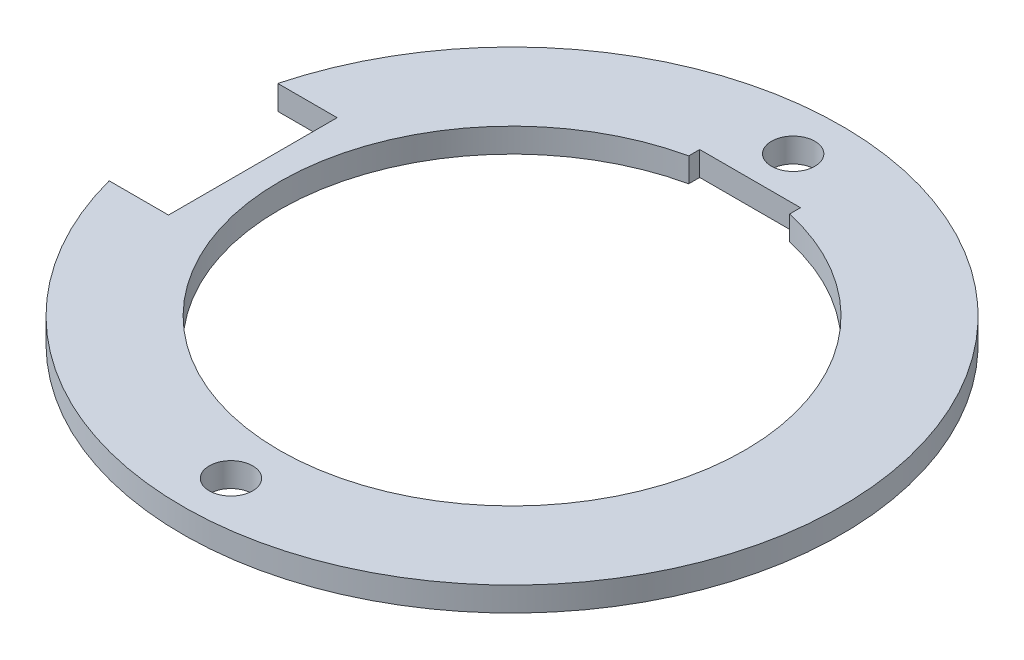
SolidWorks part; units mm, degrees
ref_plane "Front" through (0, 0, 0) normal (0, 0, 1) x (1, 0, 0)
ref_plane "Top" through (0, 0, 0) normal (0, 1, 0) x (1, 0, 0)
ref_plane "Right" through (0, 0, 0) normal (1, 0, 0) x (0, 0, -1)
sketch "Sketch1" plane through (0, 0, 0) normal (0, 1, 0) x (1, 0, 0)
  line L0 (0, -15.24) -> (0, 15.5956) construction
  line L1 (-3.302, 15.5956) -> (3.302, 15.5956)
  line L2 (-3.302, 15.5956) -> (-3.302, 14.878)
  line L3 (3.302, 15.5956) -> (3.302, 14.878)
  circle A0 centre (0, 0) radius 15.24
  circle A1 centre (0, 0) radius 21.59
  dimension "D1" = 30.48
  dimension "D3" = 30.8356
  dimension "D4" = 6.604
  dimension "D2" = 6.35
extrude "Boss-Extrude1" add sketch "Sketch1" along normal mid plane 1.5875 contours A1 A0 L2 L1 L3
sketch "Sketch2" plane through (0, 0.7937, 0) normal (0, 1, 0) x (1, 0, 0)
  line L0 (0, 18.415) -> (0, -18.415) construction
  line L1 (0, -15.24) -> (0, -21.59) construction
  circle A0 centre (0, 18.415) radius 1.4224
  circle A1 centre (0, -18.415) radius 1.4224
  arc A2 (-3.302, 14.878) -> (3.302, 14.878) centre (0, 0) ccw construction
  circle A3 centre (0, 0) radius 21.59 construction
  dimension "D1" = 2.8448
extrude "Cut-Extrude1" cut sketch "Sketch2" against normal through all
sketch "Sketch3" plane through (0, 0.7937, 0) normal (0, 1, 0) x (1, 0, 0)
  line L0 (-20.8712, 5.5245) -> (-16.9841, 5.5245)
  line L1 (-16.9841, 5.5245) -> (-16.9841, -5.5245)
  line L2 (-16.9841, -5.5245) -> (-20.8712, -5.5245)
  line L3 (-16.9841, -5.5245) -> (-20.8712, -5.5245) construction
  line L4 (-20.8712, 5.5245) -> (-16.9841, 5.5245) construction
  circle A0 centre (0, 0) radius 21.59 construction
  arc A1 (-20.8712, 5.5245) -> (-20.8712, -5.5245) centre (0, 0) ccw
extrude "Cut-Extrude2" cut sketch "Sketch3" against normal through all
